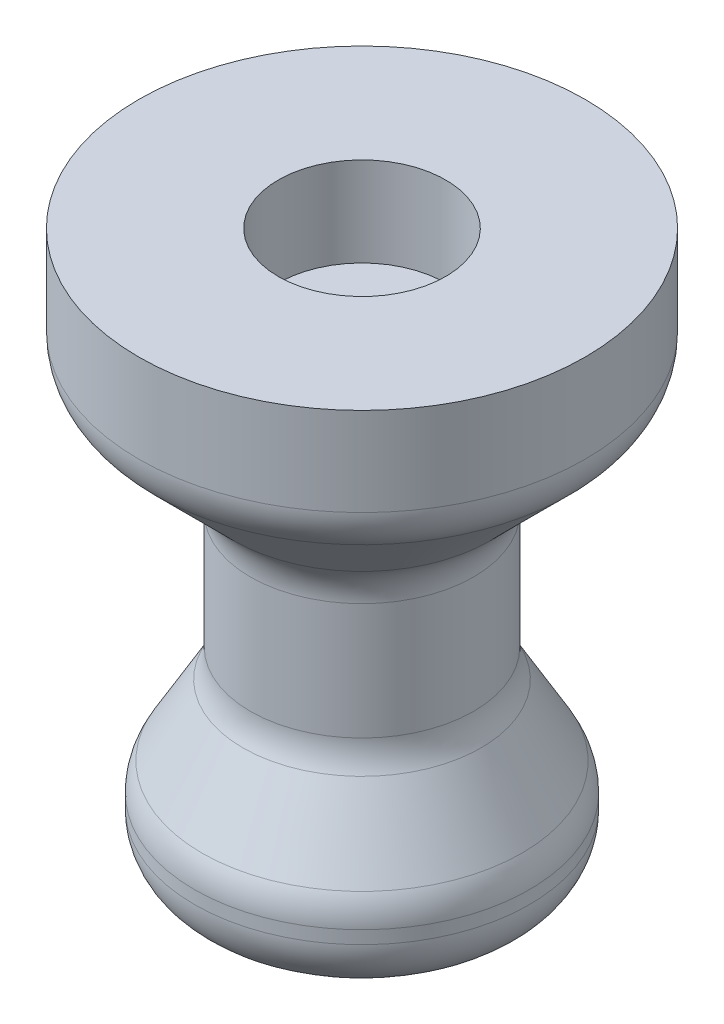
SolidWorks part; units mm, degrees
ref_plane "Front Plane" through (0, 0, 0) normal (0, 0, 1) x (1, 0, 0)
ref_plane "Top Plane" through (0, 0, 0) normal (0, 1, 0) x (1, 0, 0)
ref_plane "Right Plane" through (0, 0, 0) normal (1, 0, 0) x (0, 0, -1)
sketch "Sketch1" plane through (0, 0, 0) normal (0, 0, 1) x (1, 0, 0)
  line L0 (0, 48.586) -> (0, -39.4546) construction
  line L1 (0, 0) -> (8, 0)
  line L2 (8, 0) -> (8, -4)
  line L3 (8, -4) -> (4, -8)
  line L4 (4, -8) -> (4, -13.5359)
  line L5 (4, -13.5359) -> (6, -17)
  line L6 (6, -17) -> (6, -20)
  line L7 (6, -20) -> (0, -20)
  line L8 (0, 0) -> (0, -20)
  dimension "D1" = 8
  dimension "D2" = 20
  dimension "D3" = 8
  dimension "D4" = 12
  dimension "D5" = 30
  dimension "D6" = 135
  dimension "D7" = 4
  dimension "D8" = 3
revolve "Revolve1" add sketch "Sketch1" angle 360 about L0
fillet "Fillet1" radius 2 5 edges at (0, -4, 8) (0, -20, 6) (0, -17, 6) (0, -13.5359, 4) (0, -8, 4)
sketch "Sketch2" plane through (0, 0, 0) normal (0, 1, 0) x (1, 0, 0)
  circle A0 centre (0, 0) radius 3
  dimension "D1" = 6
extrude "Cut-Extrude1" cut sketch "Sketch2" against normal blind 3.2
